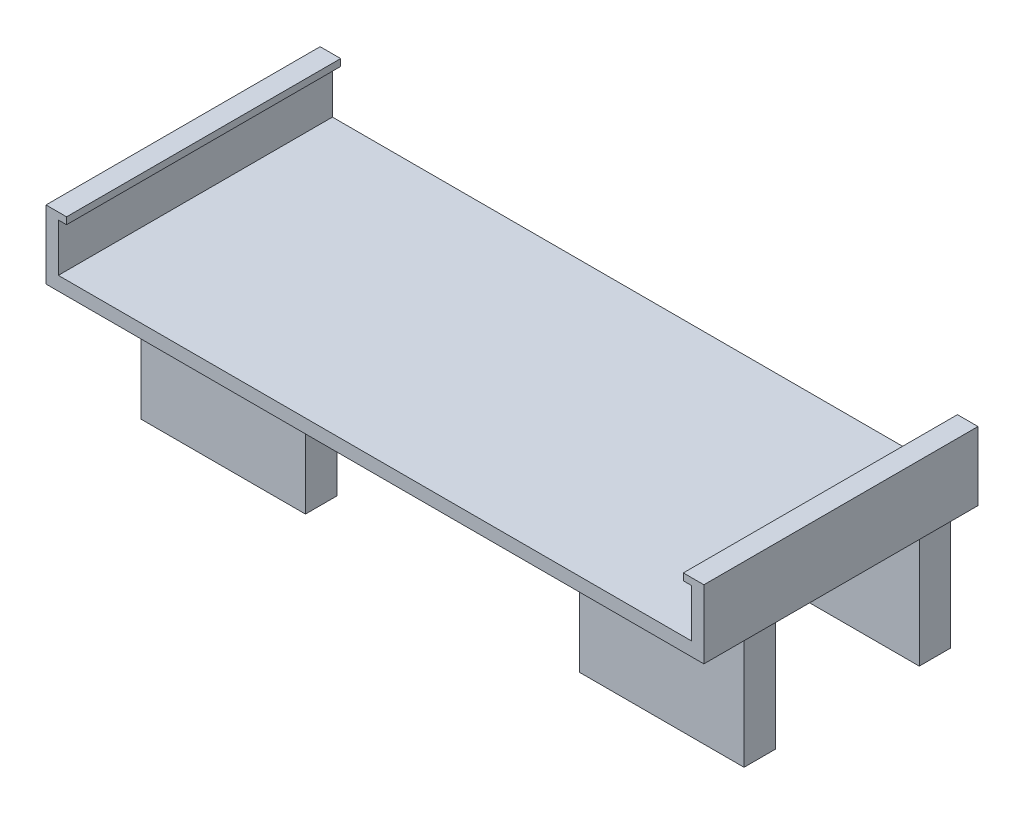
SolidWorks part; units mm, degrees
ref_plane "前视基准面" through (0, 0, 0) normal (0, 0, 1) x (1, 0, 0)
ref_plane "上视基准面" through (0, 0, 0) normal (0, 1, 0) x (1, 0, 0)
ref_plane "右视基准面" through (0, 0, 0) normal (1, 0, 0) x (0, 0, -1)
sketch "草图1" plane through (0, 0, 0) normal (0, 1, 0) x (1, 0, 0)
  line L1 (-24.78, 14.6257) -> (23.22, 14.6257)
  line L2 (-24.78, 14.6257) -> (-24.78, -5.3743)
  line L3 (-24.78, -5.3743) -> (23.22, -5.3743)
  line L4 (23.22, 14.6257) -> (23.22, -5.3743)
  dimension "D1" = 48
  dimension "D2" = 20
extrude "凸台-拉伸1" add sketch "草图1" along normal blind 5
sketch "草图2" plane through (0, 0, 5.3743) normal (0, 0, 1) x (1, 0, 0)
  line L7 (-23.28, 5) -> (-23.28, 4.5)
  line L8 (-24.78, 5) -> (23.22, 5) construction
  line L9 (-23.28, 4.5) -> (-23.88, 4.5)
  line L10 (-23.88, 4.5) -> (-23.88, 1)
  line L11 (-23.88, 1) -> (22.32, 1)
  line L12 (22.32, 1) -> (22.32, 4.5)
  line L13 (22.32, 4.5) -> (21.72, 4.5)
  line L14 (21.72, 4.5) -> (21.72, 5)
  line L15 (21.72, 5) -> (-23.28, 5)
  line L16 (23.22, 5) -> (23.22, 0) construction
  line L17 (-24.78, 5) -> (-24.78, 0) construction
  line L18 (-24.78, 0) -> (23.22, 0) construction
  dimension "D1" = 1.5
  dimension "D2" = 1.5
  dimension "D3" = 0.6
  dimension "D4" = 0.6
  dimension "D5" = 0.5
  dimension "D6" = 1
extrude "切除-拉伸1" cut sketch "草图2" against normal through all
sketch "草图3" plane through (0, 0, 0) normal (0, -1, 0) x (1, 0, 0)
  line L6 (-22.78, 0.4443) -> (-22.78, -14.6257)
  line L7 (23.22, -14.6257) -> (-24.78, -14.6257) construction
  line L8 (-22.78, -14.6257) -> (-10.78, -14.6257)
  line L9 (-10.78, -14.6257) -> (-10.78, 0.4443)
  line L10 (-10.78, 0.4443) -> (-22.78, 0.4443)
  line L11 (9.22, 0.4443) -> (9.22, -14.6257)
  line L12 (9.22, -14.6257) -> (21.22, -14.6257)
  line L13 (21.22, -14.6257) -> (21.22, 0.4443)
  line L14 (21.22, 0.4443) -> (9.22, 0.4443)
  line L15 (-24.78, -14.6257) -> (-24.78, 5.3743) construction
  dimension "D1" = 12
  dimension "D2" = 12
  dimension "D3" = 20
  dimension "D4" = 2
  dimension "D5" = 15.07
  dimension "D6" = 15.07
extrude "凸台-拉伸2" add sketch "草图3" along normal blind 10
sketch "草图4" plane through (21.22, 0, 0) normal (1, 0, 0) x (0, 0, -1)
  line L0 (1.8407, -2) -> (1.8407, -10)
  line L1 (14.6257, -10) -> (-0.4443, -10) construction
  line L2 (1.8407, -10) -> (12.3407, -10)
  line L3 (12.3407, -10) -> (12.3407, -2)
  line L4 (12.3407, -2) -> (1.8407, -2)
  line L5 (14.6257, -10) -> (14.6257, 0) construction
  point P8 (14.6257, -5)
  dimension "D1" = 8
  dimension "D2" = 10.5
  dimension "D3" = 2.285
extrude "切除-拉伸2" cut sketch "草图4" against normal through all
